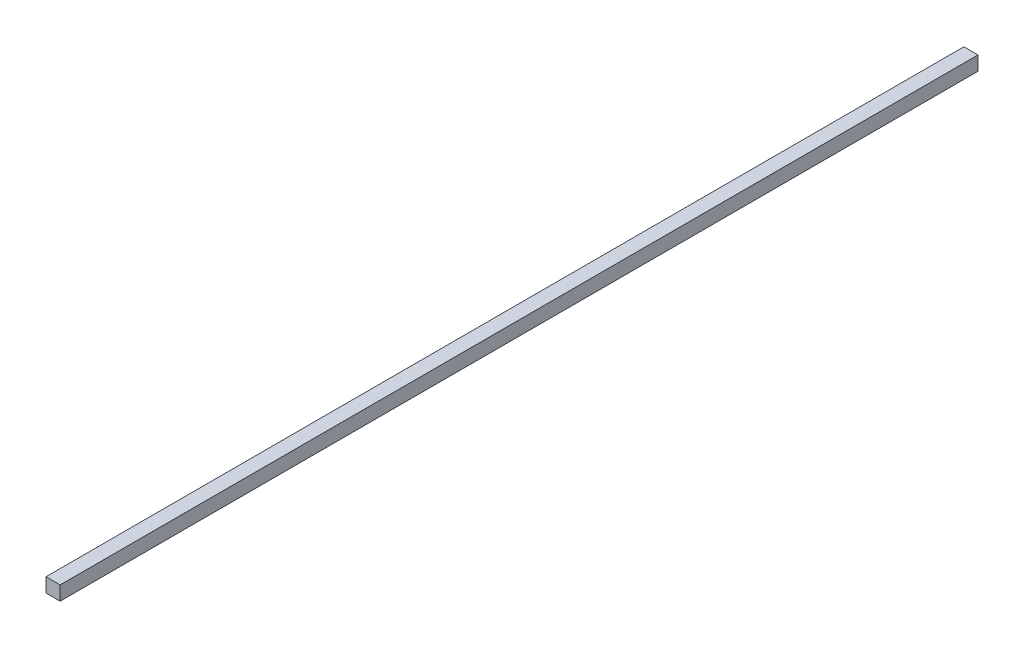
SolidWorks part; units mm, degrees
ref_plane "Front Plane" through (0, 0, 0) normal (0, 0, 1) x (1, 0, 0)
ref_plane "Top Plane" through (0, 0, 0) normal (0, 1, 0) x (1, 0, 0)
ref_plane "Right Plane" through (0, 0, 0) normal (1, 0, 0) x (0, 0, -1)
sketch "Sketch1" plane through (0, 0, 0) normal (0, 0, 1) x (1, 0, 0)
  line L1 (-10, 10) -> (10, 10)
  line L2 (-10, 10) -> (-10, -10)
  line L3 (-10, -10) -> (10, -10)
  line L4 (10, 10) -> (10, -10)
  line L5 (-10, 10) -> (10, -10) construction
  line L6 (-10, -10) -> (10, 10) construction
  point P0 (0, 0)
  dimension "D1" = 20
  dimension "D2" = 20
extrude "Boss-Extrude1" add sketch "Sketch1" along normal blind 1300
